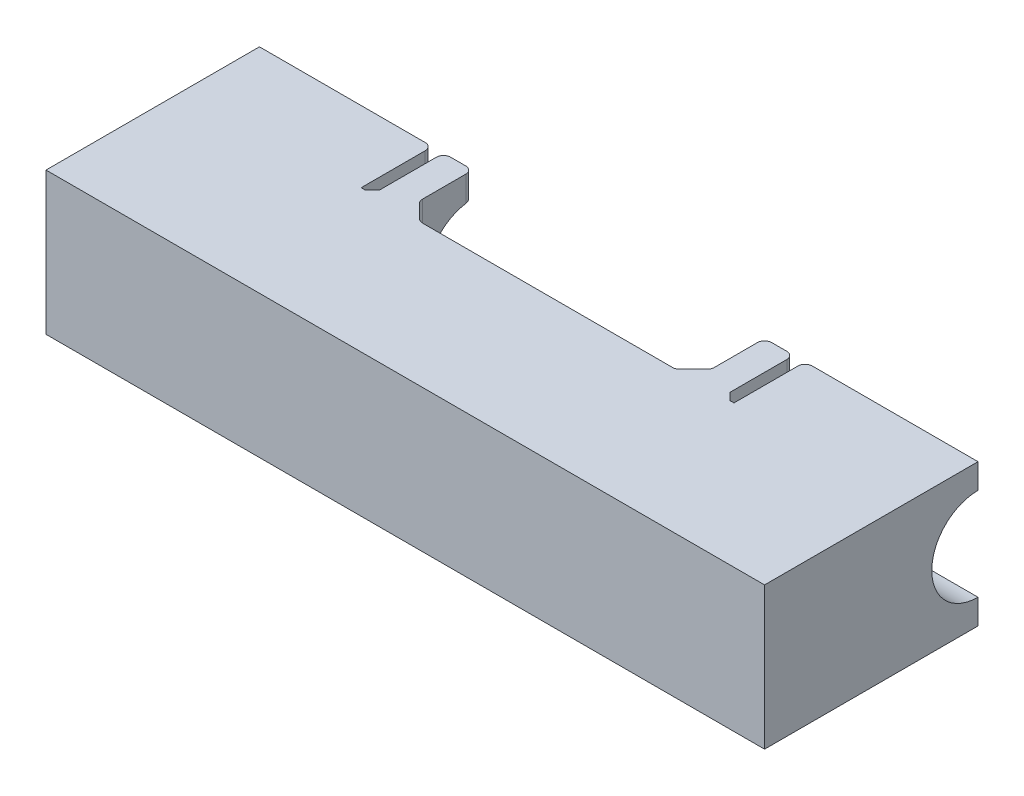
SolidWorks part; units mm, degrees
material "ABS"
ref_plane "Front Plane" through (0, 0, 0) normal (0, 0, 1) x (1, 0, 0)
ref_plane "Top Plane" through (0, 0, 0) normal (0, 1, 0) x (1, 0, 0)
ref_plane "Right Plane" through (0, 0, 0) normal (1, 0, 0) x (0, 0, -1)
sketch "Sketch1" plane through (0, 0, 0) normal (0, 1, 0) x (1, 0, 0)
  line L0 (41, 0) -> (-41, 0)
  line L1 (-41, 0) -> (-41, 20)
  line L3 (-101, 20) -> (-101, -40)
  line L9 (-41, 20) -> (-49.25, 20)
  line L10 (-49.25, 20) -> (-49.25, 0)
  line L11 (-49.25, 0) -> (-52.4, 0)
  line L12 (-52.4, 0) -> (-52.4, 20)
  line L13 (-52.4, 20) -> (-101, 20)
  line L14 (-101, -40) -> (101, -40)
  line L15 (0, -40) -> (0, 0) construction
  line L16 (52.4, 20) -> (101, 20)
  line L17 (52.4, 0) -> (52.4, 20)
  line L18 (49.25, 0) -> (52.4, 0)
  line L19 (49.25, 20) -> (49.25, 0)
  line L20 (41, 20) -> (49.25, 20)
  line L21 (101, 20) -> (101, -40)
  line L22 (41, 0) -> (41, 20)
  dimension "D1" = 41
  dimension "D2" = 40
  dimension "D3" = 3.15
  dimension "D4" = 48.6
  dimension "D5" = 60
  dimension "D6" = 60
extrude "Boss-Extrude1" add sketch "Sketch1" along normal blind 40
sketch "Sketch2" plane through (-101, 0, 0) normal (-1, 0, 0) x (0, 0, 1)
  line L0 (-20, 40) -> (-20, 0) construction
  line L1 (40, 20) -> (-7, 20) construction
  line L2 (40, 40) -> (40, 0) construction
  circle A0 centre (-20, 20) radius 13
  dimension "D1" = 47
extrude "Cut-Extrude1" cut sketch "Sketch2" against normal through all
chamfer "Chamfer1" distance 5 angle 45 2 edges at (41, 20, 0) (-41, 20, 0)
fillet "Fillet3" radius 2 16 edges at (36, 20, 0) (-36, 20, 0) (41, 20, -5) (-41, 20, -5) (-52.4, 36.5, -20) (-52.4, 3.5, -20) (-49.25, 3.5, -20) (-41, 3.5, -20) (-41, 36.5, -20) (52.4, 36.5, -20) (49.25, 36.5, -20) (49.25, 3.5, -20) (41, 3.5, -20) (41, 36.5, -20) (-49.25, 36.5, -20) (52.4, 3.5, -20)
chamfer "Chamfer2" distance 2 angle 45 2 edges at (-49.25, 20, 0) (49.25, 20, 0)
